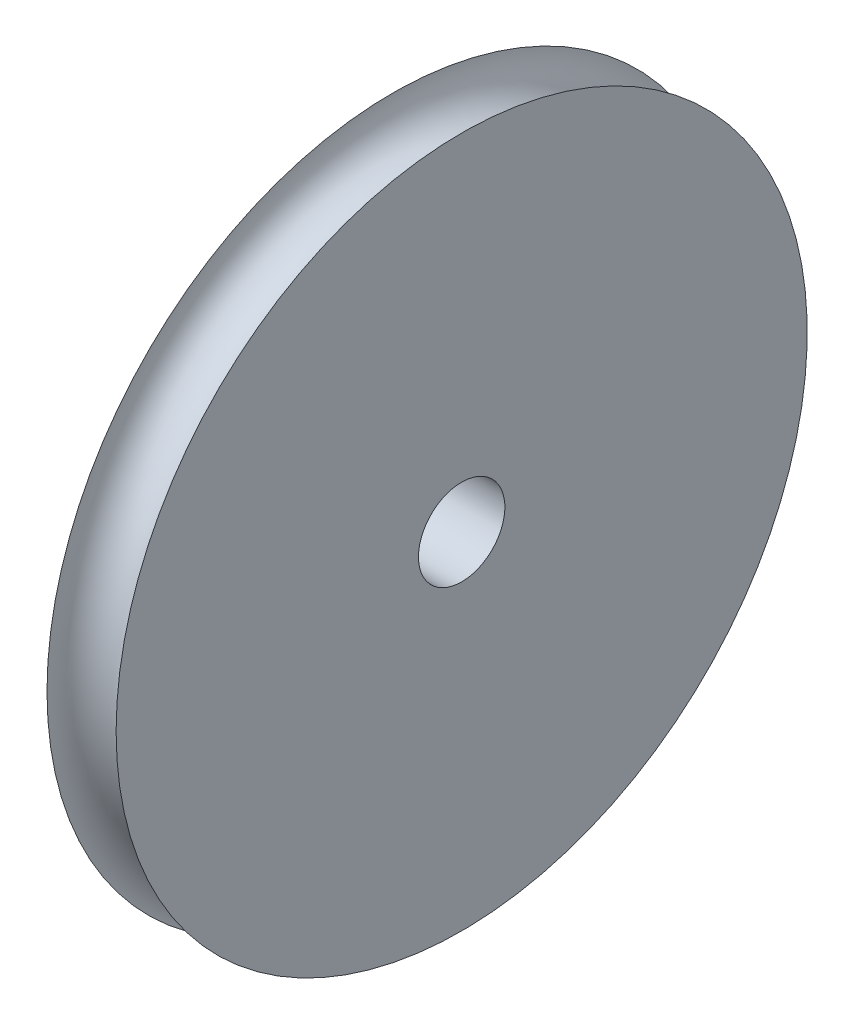
SolidWorks part; units mm, degrees
material "Alliage 1060"
ref_plane "Plan de face" through (0, 0, 0) normal (0, 0, 1) x (1, 0, 0)
ref_plane "Plan de dessus" through (0, 0, 0) normal (0, 1, 0) x (1, 0, 0)
ref_plane "Plan de droite" through (0, 0, 0) normal (1, 0, 0) x (0, 0, -1)
sketch "Esquisse1" plane through (0, 0, 0) normal (0, 0, 1) x (1, 0, 0)
  line L0 (-24.0416, 0) -> (22.9283, 0) construction
  line L1 (-5.6, 2) -> (-5.6, 5.5)
  line L2 (-5.6, 5.5) -> (-1.6, 5.5)
  line L3 (-1.6, 5.5) -> (-1.6, 16)
  line L4 (1.6, 16) -> (1.6, 2)
  line L5 (-5.6, 2) -> (1.6, 2)
  arc A0 (-1.6, 16) -> (1.6, 16) centre (0, 16) ccw
  point P3 (3.8259, 20.7683)
  dimension "D1" = 1.6
  dimension "D2" = 4
  dimension "D3" = 11
  dimension "D4" = 32
  dimension "D5" = 4
revolve "Révolution1" add sketch "Esquisse1" angle 360 about L0
hole_wizard "Trou taraudé M3x0.51" positions "Esquisse3" profile "Esquisse2" tap size "M3x0.5" standard "Ansi Métrique"
sketch "Esquisse3" plane through (0, 0, 0) normal (0, 0, 1) x (1, 0, 0)
  line L3 (-1.6, 5.5) -> (-1.6, -5.5) construction
  point P0 (-3.6, 0)
  dimension "D1" = 2
sketch "Esquisse2" plane through (-3.6, 0, 0) normal (1, 0, 0) x (0, 1, 0)
  line L0 (0, 0) -> (0, 16)
  line L1 (0, 16) -> (1.25, 16)
  line L2 (1.25, 16) -> (1.25, 0)
  line L5 (1.25, 0) -> (0, 0)
  line L11 (0, -6.35) -> (0, 107.95) construction
  dimension "Diamètre du trou pour taraudage jusqu'au prochain" = 2.5
  dimension "Profondeur du trou pour taraudage jusqu'au prochain" = 16
cosmetic thread "Filetage de perçage1"
